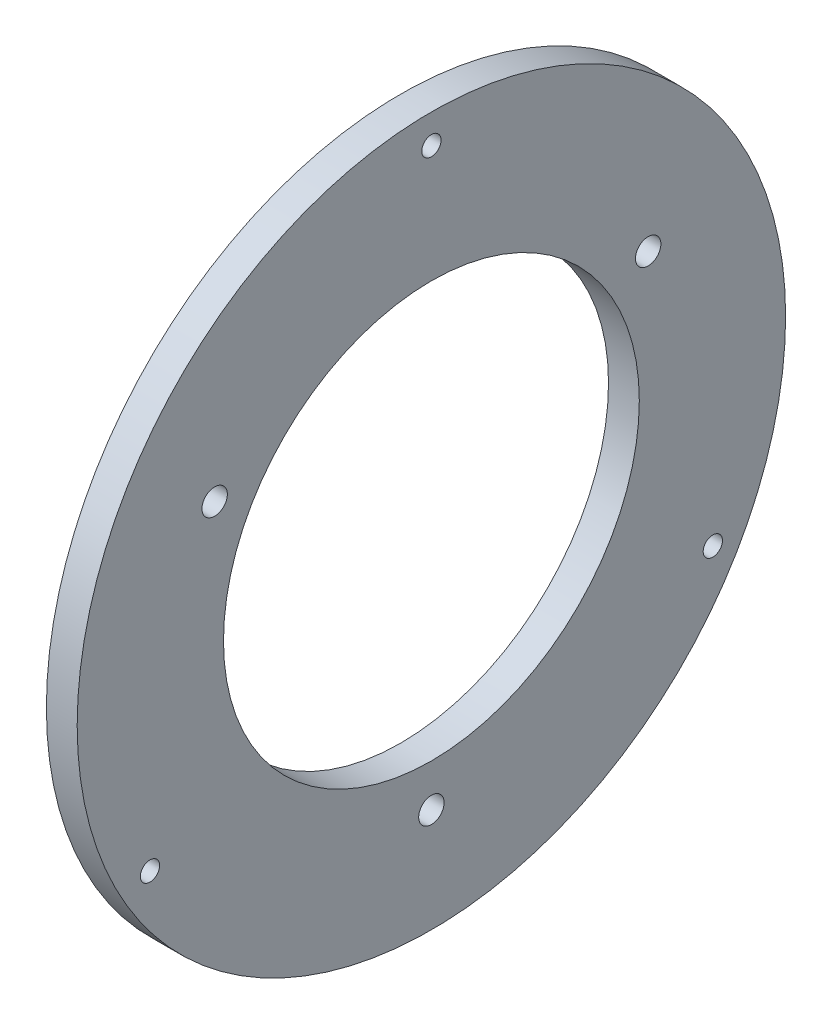
SolidWorks part; units mm, degrees
material "AISI 304"
ref_plane "Front Plane" through (0, 0, 0) normal (0, 0, 1) x (1, 0, 0)
ref_plane "Top Plane" through (0, 0, 0) normal (0, 1, 0) x (1, 0, 0)
ref_plane "Right Plane" through (0, 0, 0) normal (1, 0, 0) x (0, 0, -1)
sketch "Axial profile (mm)" plane through (0, 0, 0) normal (0, 0, 1) x (1, 0, 0)
  line L0 (-110, 0) -> (75, 0) construction
  line L1 (131.7, 27) -> (135.7, 27)
  line L2 (135.7, 27) -> (135.7, 46)
  line L3 (135.7, 46) -> (131.7, 46)
  line L4 (131.7, 46) -> (131.7, 27)
revolve "Full revolution" add sketch "Axial profile (mm)" angle 360 about L0
sketch "Sketch2" plane through (0, 0, 0) normal (1, 0, 0) x (0, 0, -1)
  circle A0 centre (0, 42.2) radius 1.25
  circle A1 centre (-36.5463, -21.1) radius 1.25
  circle A2 centre (36.5463, -21.1) radius 1.25
  circle A3 centre (-28.1458, 16.25) radius 1.65
  circle A4 centre (0, -32.5) radius 1.65
  circle A5 centre (28.1458, 16.25) radius 1.65
extrude "Axial holes" cut sketch "Sketch2" along normal through all and the other way through all
